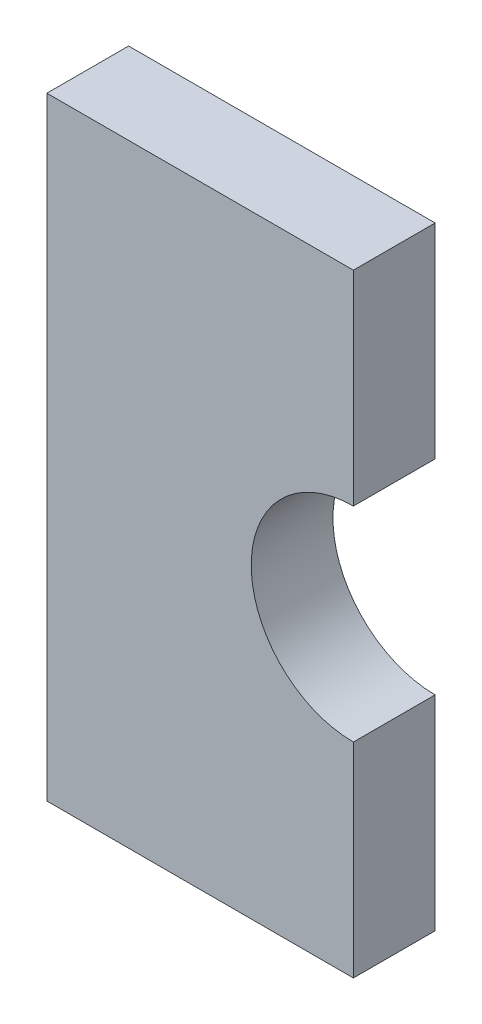
SolidWorks part; units mm, degrees
ref_plane "Front Plane" through (0, 0, 0) normal (0, 0, 1) x (1, 0, 0)
ref_plane "Top Plane" through (0, 0, 0) normal (0, 1, 0) x (1, 0, 0)
ref_plane "Right Plane" through (0, 0, 0) normal (1, 0, 0) x (0, 0, -1)
sketch "Sketch1" plane through (0, 0, 0) normal (0, 0, 1) x (1, 0, 0)
  line L0 (0, 5) -> (0, 15)
  line L1 (0, 15) -> (-15, 15)
  line L2 (-15, 15) -> (-15, -15)
  line L3 (-15, -15) -> (0, -15)
  line L4 (0, -15) -> (0, -5)
  arc A0 (0, 5) -> (0, -5) centre (0, 0) ccw
  dimension "D1" = 10
  dimension "D2" = 10
  dimension "D3" = 10
  dimension "D4" = 15
extrude "Boss-Extrude1" add sketch "Sketch1" along normal blind 4
